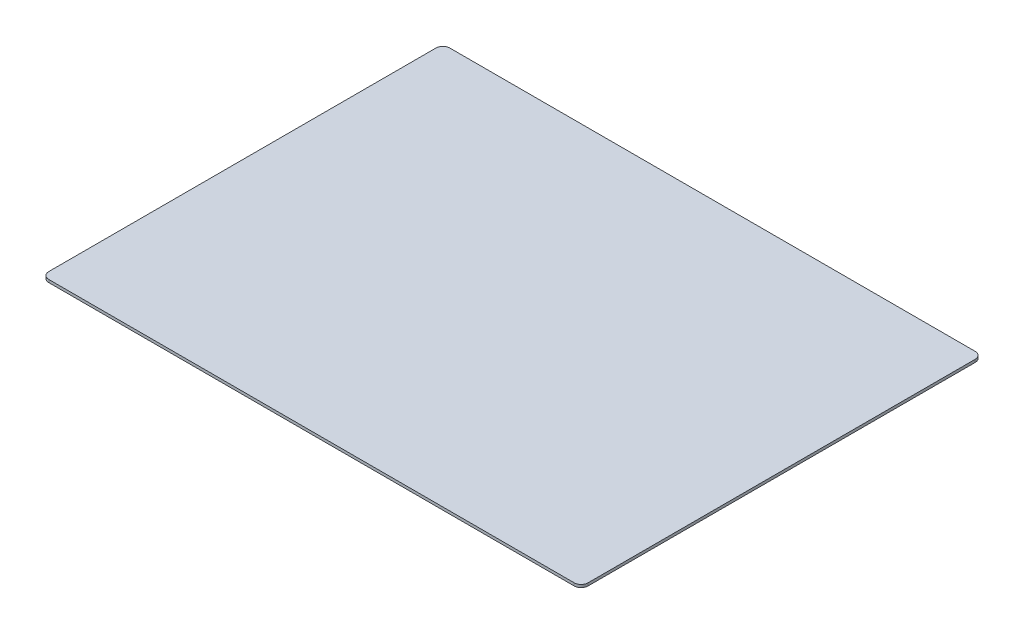
SolidWorks part; units mm, degrees
ref_plane "정면" through (0, 0, 0) normal (0, 0, 1) x (1, 0, 0)
ref_plane "윗면" through (0, 0, 0) normal (0, 1, 0) x (1, 0, 0)
ref_plane "우측면" through (0, 0, 0) normal (1, 0, 0) x (0, 0, -1)
sketch "스케치1" plane through (0, 0, 0) normal (0, 1, 0) x (1, 0, 0)
  line L1 (-195, -145) -> (195, -145)
  line L2 (-195, -145) -> (-195, 145)
  line L3 (-195, 145) -> (195, 145)
  line L4 (195, -145) -> (195, 145)
  line L5 (-195, -145) -> (195, 145) construction
  line L6 (-195, 145) -> (195, -145) construction
  point P0 (0, 0)
  dimension "D1" = 290
  dimension "D2" = 390
extrude "보스-돌출1" add sketch "스케치1" along normal blind 2
fillet "필렛1" radius 5 4 edges at (195, 1, -145) (195, 1, 145) (-195, 1, -145) (-195, 1, 145)
